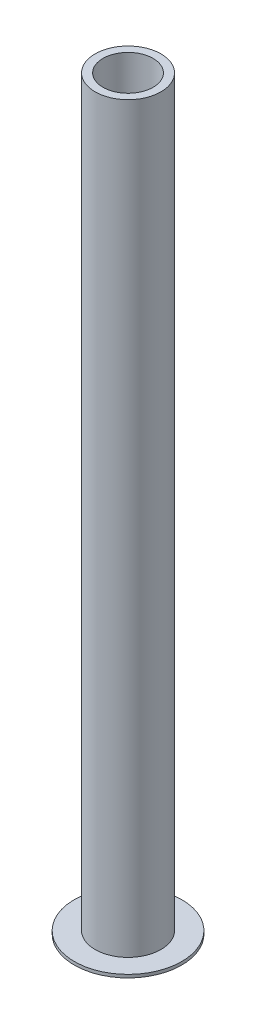
SolidWorks part; units mm, degrees
ref_plane "Front Plane" through (0, 0, 0) normal (0, 0, 1) x (1, 0, 0)
ref_plane "Top Plane" through (0, 0, 0) normal (0, 1, 0) x (1, 0, 0)
ref_plane "Right Plane" through (0, 0, 0) normal (1, 0, 0) x (0, 0, -1)
sketch "Sketch1" plane through (0, 0, 0) normal (0, 1, 0) x (1, 0, 0)
  circle A0 centre (0, 0) radius 4.064
  circle A1 centre (0, 0) radius 5.334
  dimension "D1" = 8.128
  dimension "D2" = 1.27
extrude "Boss-Extrude1" add sketch "Sketch1" along normal blind 120.396
sketch "Sketch2" plane through (0, 0, 0) normal (0, -1, 0) x (1, 0, 0)
  circle A0 centre (0, 0) radius 8.6995
  circle A1 centre (0, 0) radius 4.064
  dimension "D1" = 17.399
extrude "Boss-Extrude2" add sketch "Sketch2" along normal blind 0.508
